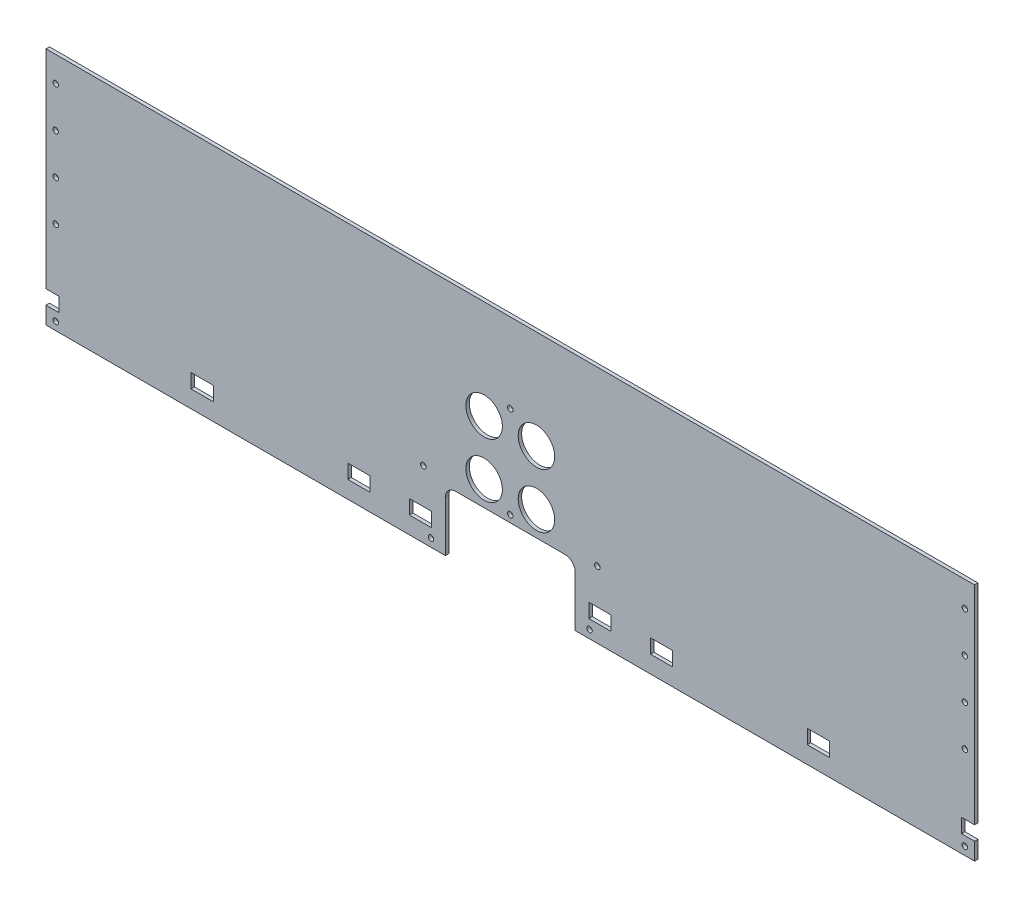
SolidWorks part; units mm, degrees
ref_plane "Front Plane" through (0, 0, 0) normal (0, 0, 1) x (1, 0, 0)
ref_plane "Top Plane" through (0, 0, 0) normal (0, 1, 0) x (1, 0, 0)
ref_plane "Right Plane" through (0, 0, 0) normal (1, 0, 0) x (0, 0, -1)
sketch "Sketch2" plane through (0, 0, 0) normal (0, 1, 0) x (1, 0, 0)
  line L0 (0, 0) -> (0, -85) construction
  line L1 (-30.03, -64.8129) -> (30.03, -64.8129)
  line L2 (0, 0) -> (-42.6144, -58.6537) construction
  line L3 (0, 0) -> (-62.7868, -36.25) construction
  line L4 (0, 0) -> (-62.7868, 36.25) construction
  line L5 (-30.03, -66.5129) -> (30.03, -66.5129)
  arc A0 (34.8348, -63.5829) -> (-34.8348, -63.5829) centre (0, 0) ccw
  circle A1 centre (0, -85) radius 38.25 construction
  arc A2 (-30.03, -64.8129) -> (-34.8348, -63.5829) centre (-30.03, -54.8129) cw
  arc A3 (34.8348, -63.5829) -> (30.03, -64.8129) centre (30.03, -54.8129) cw
  arc A4 (35.6516, -65.0738) -> (30.03, -66.5129) centre (30.03, -54.8129) cw
  arc A5 (35.6516, -65.0738) -> (-35.6516, -65.0738) centre (0, 0) ccw
  arc A6 (-30.03, -66.5129) -> (-35.6516, -65.0738) centre (-30.03, -54.8129) cw
  point P8 (32.4891, -64.8129)
  dimension "D1" = 145
  dimension "D2" = 76.5
  dimension "D4" = 10
  dimension "D3" = 85
  dimension "D5" = 36
  dimension "D6" = 24
  dimension "D7" = 60
  dimension "D8" = 1.7
sketch "Sketch3" plane through (0, 0, 0) normal (0, 0, 1) x (1, 0, 0)
  line L1 (-229, -59) -> (229, -59)
  line L2 (-229, -59) -> (-229, 59)
  line L3 (-229, 59) -> (229, 59)
  line L4 (229, -59) -> (229, 59)
  line L5 (-229, -59) -> (229, 59) construction
  line L6 (-229, 59) -> (229, -59) construction
  point P0 (0, 0)
  dimension "D1" = 458
  dimension "D2" = 118
extrude "Boss-Extrude2" add sketch "Sketch3" along normal blind 1.7
sketch "Sketch4" plane through (0, 0, 1.7) normal (0, 0, 1) x (1, 0, 0)
  line L0 (0, -59) -> (0, 19.8) construction
  line L1 (-229, -59) -> (229, -59) construction
  line L2 (229, 59) -> (-229, 59) construction
  circle A0 centre (0, 19.8) radius 1.35
  circle A1 centre (0, -25.5) radius 1.35
  circle A2 centre (39.1, -55) radius 1.35
  circle A3 centre (42.9, -26) radius 1.35
  circle A4 centre (224.2, -55) radius 1.35
  circle A5 centre (-224.2, -55) radius 1.35
  circle A6 centre (-42.9, -26) radius 1.35
  circle A7 centre (-39.1, -55) radius 1.35
  circle A8 centre (224.2, 46.5) radius 1.35
  circle A9 centre (224.2, 26.5) radius 1.35
  circle A10 centre (224.2, 6.5) radius 1.35
  circle A11 centre (224.2, -13.5) radius 1.35
  circle A12 centre (-224.2, -13.5) radius 1.35
  circle A13 centre (-224.2, 6.5) radius 1.35
  circle A14 centre (-224.2, 26.5) radius 1.35
  circle A15 centre (-224.2, 46.5) radius 1.35
  dimension "D1" = 2.7
  dimension "D2" = 78.8
  dimension "D3" = 33.5
  dimension "D4" = 39.1
  dimension "D5" = 4
  dimension "D6" = 42.9
  dimension "D7" = 33
  dimension "D8" = 224.2
  dimension "D9" = 4
  dimension "D10" = 12.5
  dimension "D12" = 20
  dimension "D11" = 4
extrude "Cut-Extrude1" cut sketch "Sketch4" against normal through all
sketch "Sketch5" plane through (0, 0, 1.7) normal (0, 0, 1) x (1, 0, 0)
  line L0 (-229, -59) -> (229, -59) construction
  line L1 (-32, -59) -> (32, -59)
  line L2 (-32, -59) -> (-32, -34)
  line L3 (-27, -29) -> (27, -29)
  line L4 (32, -59) -> (32, -34)
  arc A0 (27, -29) -> (32, -34) centre (27, -34) cw
  arc A1 (-32, -34) -> (-27, -29) centre (-27, -34) cw
  point P6 (0, -29)
  point P10 (32, -29)
  dimension "D3" = 5
  dimension "D1" = 64
  dimension "D2" = 30
extrude "Cut-Extrude2" cut sketch "Sketch5" against normal through all
sketch "Sketch6" plane through (0, 0, 1.7) normal (0, 0, 1) x (1, 0, 0)
  line L0 (-229, -59) -> (-32, -59) construction
  line L1 (0, 0) -> (0, -29) construction
  line L2 (27, -29) -> (-27, -29) construction
  circle A0 centre (-12.9, -16.75) radius 9
  circle A1 centre (-12.9, 10.25) radius 9
  circle A2 centre (12.9, -16.75) radius 9
  circle A3 centre (12.9, 10.25) radius 9
  dimension "D2" = 18
  dimension "D1" = 42.25
  dimension "D3" = 12.9
  dimension "D4" = 27
extrude "Cut-Extrude3" cut sketch "Sketch6" against normal through all
sketch "Sketch8" plane through (0, 0, 1.7) normal (0, 0, 1) x (1, 0, 0)
  line L0 (-229, -59) -> (-32, -59) construction
  line L1 (-49.76, -50.5) -> (-38.76, -50.5)
  line L2 (-49.76, -50.5) -> (-49.76, -43.5)
  line L3 (-49.76, -43.5) -> (-38.76, -43.5)
  line L4 (-38.76, -50.5) -> (-38.76, -43.5)
  line L5 (-49.76, -50.5) -> (-38.76, -43.5) construction
  line L6 (-49.76, -43.5) -> (-38.76, -50.5) construction
  line L7 (0, 0) -> (0, 59) construction
  line L8 (-80.13, -50.5) -> (-69.13, -50.5)
  line L9 (-80.13, -50.5) -> (-80.13, -43.5)
  line L10 (-80.13, -43.5) -> (-69.13, -43.5)
  line L11 (-69.13, -50.5) -> (-69.13, -43.5)
  line L12 (-80.13, -50.5) -> (-69.13, -43.5) construction
  line L13 (-80.13, -43.5) -> (-69.13, -50.5) construction
  line L14 (-157.5, -50.5) -> (-146.5, -50.5)
  line L15 (-157.5, -50.5) -> (-157.5, -43.5)
  line L16 (-157.5, -43.5) -> (-146.5, -43.5)
  line L17 (-146.5, -50.5) -> (-146.5, -43.5)
  line L18 (-157.5, -50.5) -> (-146.5, -43.5) construction
  line L19 (-157.5, -43.5) -> (-146.5, -50.5) construction
  line L20 (-233.5, -50.5) -> (-222.5, -50.5)
  line L21 (-233.5, -50.5) -> (-233.5, -43.5)
  line L22 (-233.5, -43.5) -> (-222.5, -43.5)
  line L23 (-222.5, -50.5) -> (-222.5, -43.5)
  line L24 (-233.5, -50.5) -> (-222.5, -43.5) construction
  line L25 (-233.5, -43.5) -> (-222.5, -50.5) construction
  line L26 (229, 59) -> (-229, 59) construction
  line L27 (233.5, -43.5) -> (222.5, -50.5) construction
  line L28 (233.5, -50.5) -> (222.5, -43.5) construction
  line L29 (157.5, -43.5) -> (146.5, -50.5) construction
  line L30 (157.5, -50.5) -> (146.5, -43.5) construction
  line L31 (80.13, -43.5) -> (69.13, -50.5) construction
  line L32 (80.13, -50.5) -> (69.13, -43.5) construction
  line L33 (49.76, -43.5) -> (38.76, -50.5) construction
  line L34 (49.76, -50.5) -> (38.76, -43.5) construction
  line L35 (222.5, -50.5) -> (222.5, -43.5)
  line L36 (233.5, -43.5) -> (222.5, -43.5)
  line L37 (233.5, -50.5) -> (233.5, -43.5)
  line L38 (233.5, -50.5) -> (222.5, -50.5)
  line L39 (146.5, -50.5) -> (146.5, -43.5)
  line L40 (157.5, -43.5) -> (146.5, -43.5)
  line L41 (157.5, -50.5) -> (157.5, -43.5)
  line L42 (157.5, -50.5) -> (146.5, -50.5)
  line L43 (69.13, -50.5) -> (69.13, -43.5)
  line L44 (80.13, -43.5) -> (69.13, -43.5)
  line L45 (80.13, -50.5) -> (80.13, -43.5)
  line L46 (80.13, -50.5) -> (69.13, -50.5)
  line L47 (38.76, -50.5) -> (38.76, -43.5)
  line L48 (49.76, -43.5) -> (38.76, -43.5)
  line L49 (49.76, -50.5) -> (49.76, -43.5)
  line L50 (49.76, -50.5) -> (38.76, -50.5)
  point P0 (-44.26, -47)
  point P8 (-74.63, -47)
  point P13 (-152, -47)
  point P18 (-228, -47)
  point P43 (228, -47)
  point P44 (152, -47)
  point P45 (74.63, -47)
  point P46 (44.26, -47)
  dimension "D1" = 44.26
  dimension "D2" = 11
  dimension "D3" = 7
  dimension "D4" = 12
  dimension "D5" = 74.63
  dimension "D6" = 152
  dimension "D7" = 228
extrude "Cut-Extrude4" cut sketch "Sketch8" against normal through all
equation "\"smallPulleyTeeth\"= 30"
equation "\"largePulleyTeeth\"= 30"
equation "\"eighthThick\"= 3.0mm"
equation "\"sixteenthThick\" = 1.7mm"
equation "\"quarterThick\"=6.0mm"
equation "\"OD\" = 145mm"
equation "\"puckAngle\" = 60.5deg"
equation "\"puckDiam\" = 76.5mm"
equation "\"puckDist\" = 85mm"
equation "\"scoopFillet\" = 5mm"
equation "\"axlePress\" = 5.9mm"
equation "\"press\" = 0.2mm"
equation "\"wheelClear\" = 0.3mm"
equation "\"10-32clear\" = 4.8mm"
equation "\"10-32tap\" = 4.45mm"
equation "\"6-32clear\" = 3.3mm"
equation "\"8-32clear\" = 4.0mm"
equation "\"4-40clear\" = 3.0mm"
equation "\"wheelHeight\" = 22mm"
equation "\"wheelWell\" = 65mm"
equation "\"ledSmall\" = 3.1mm"
equation "\"ledLarge\" = 4.2mm"
equation "\"ledLength\" = 4.2mm"
equation "\"4-40close\" = 2.7mm"
equation "\"4-40nutThick\" = 2.2mm"
equation "\"4-40nutWidth\" = 6.2mm"
equation "\"4-40insertHeight\" = 3.5mm"
equation "\"4-40insert\" = 4.25mm"
equation "\"D1@Boss-Extrude2\"=\"sixteenthThick\""
equation "\"D1@Sketch4\"=\"4-40close\""
equation "\"D1@Sketch2\"=\"OD\""
equation "\"D3@Sketch2\"=\"puckDist\""
